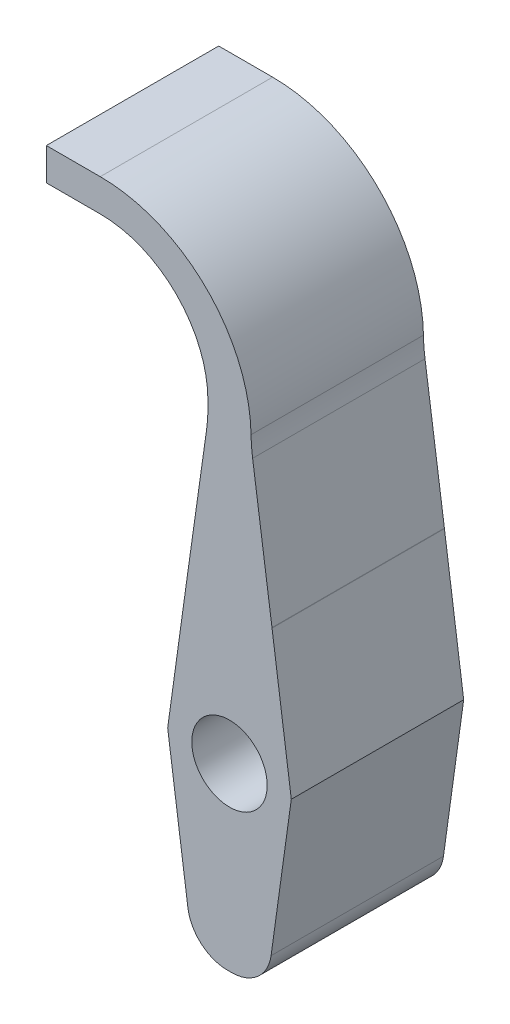
SolidWorks part; units mm, degrees
ref_plane "Front Plane" through (0, 0, 0) normal (0, 0, 1) x (1, 0, 0)
ref_plane "Top Plane" through (0, 0, 0) normal (0, 1, 0) x (1, 0, 0)
ref_plane "Right Plane" through (0, 0, 0) normal (1, 0, 0) x (0, 0, -1)
sketch "Sketch2" plane through (0, 0, 0) normal (0, 0, 1) x (1, 0, 0)
  line L0 (-2, 41.178) -> (2, 41.178)
  line L1 (0, 41.178) -> (0, 42.1099) construction
  line L2 (-0.196, 16.7) -> (0.196, 16.7) construction
  line L3 (-5.5791, 1.1332) -> (-3.8609, 13.5088) construction
  line L4 (3.8609, 13.5088) -> (5.5791, 1.1332) construction
  line L16 (-3.5, 0) -> (3.5, 0) construction
  line L17 (-3.5981, -0.8582) -> (-1.8799, -13.2338)
  line L18 (-0.196, -14.7) -> (0.196, -14.7)
  line L19 (1.8799, 13.2338) -> (3.5981, 0.8582)
  line L20 (-0.196, 14.7) -> (0.196, 14.7)
  line L21 (-3.5981, 0.8582) -> (-1.8799, 13.2338)
  line L22 (1.8799, 13.2338) -> (3.5981, 0.8582)
  line L23 (-0.196, 14.7) -> (0.196, 14.7)
  line L24 (-3.5981, 0.8582) -> (-1.8799, 13.2338)
  line L25 (1.8799, -13.2338) -> (3.5981, -0.8582)
  line L26 (3.5981, 0.8582) -> (3.7172, 0)
  line L27 (3.7172, 0) -> (3.5981, -0.8582)
  line L28 (-3.5981, 0.8582) -> (-3.7172, 0)
  line L29 (-3.7172, 0) -> (-3.5981, -0.8582)
  line L30 (-5.5791, 1.1332) -> (-3.9505, 12.8632)
  line L32 (3.9505, 12.8632) -> (5.5791, 1.1332)
  line L33 (5.5791, 1.1332) -> (5.7364, 0)
  line L34 (5.7364, 0) -> (5.5791, -1.1332)
  line L35 (3.8609, -13.5088) -> (5.5791, -1.1332)
  line L36 (-0.196, -16.7) -> (0.196, -16.7)
  line L37 (-5.5791, -1.1332) -> (-3.8609, -13.5088)
  line L38 (-5.7364, 0) -> (-5.5791, -1.1332)
  line L39 (-5.5791, 1.1332) -> (-5.7364, 0)
  line L40 (-3.9453, 12.9006) -> (-2.1478, 25.6121)
  line L41 (-2, 27.7123) -> (-2, 41.178)
  line L42 (0, -16.7) -> (0, 16.7) construction
  line L43 (3.9453, 12.9006) -> (2.1478, 25.6121)
  line L44 (2, 27.7123) -> (2, 41.178)
  arc A0 (-0.196, 16.7) -> (-3.8609, 13.5088) centre (-0.196, 13) ccw construction
  arc A1 (3.8609, 13.5088) -> (0.196, 16.7) centre (0.196, 13) ccw construction
  arc A2 (-3.9505, 12.8632) -> (-3.9453, 12.9006) centre (10.907, 10.8004) cw
  arc A3 (3.9453, 12.9006) -> (3.9505, 12.8632) centre (-10.907, 10.8004) cw
  arc A4 (2.1478, 25.6121) -> (2, 27.7123) centre (17, 27.7123) cw
  arc A5 (-2.1478, 25.6121) -> (-2, 27.7123) centre (-17, 27.7123) ccw
  circle A10 centre (0, 0) radius 3.5 construction
  arc A11 (-0.196, -14.7) -> (-1.8799, -13.2338) centre (-0.196, -13) cw
  arc A12 (1.8799, 13.2338) -> (0.196, 14.7) centre (0.196, 13) ccw
  arc A13 (-0.196, 14.7) -> (-1.8799, 13.2338) centre (-0.196, 13) ccw
  arc A14 (1.8799, 13.2338) -> (0.196, 14.7) centre (0.196, 13) ccw
  arc A15 (-0.196, 14.7) -> (-1.8799, 13.2338) centre (-0.196, 13) ccw
  arc A16 (1.8799, -13.2338) -> (0.196, -14.7) centre (0.196, -13) cw
  arc A19 (3.8609, -13.5088) -> (0.196, -16.7) centre (0.196, -13) cw
  arc A20 (-0.196, -16.7) -> (-3.8609, -13.5088) centre (-0.196, -13) cw
  point P58 (2, 26.657)
  point P61 (-2, 26.657)
  dimension "D4" = 15
  dimension "D3" = 4
  dimension "D1" = 0.2
  dimension "D2" = 2
extrude "Boss-Extrude1" add sketch "Sketch2" against normal blind 4
sketch "Sketch3" plane through (0, 0, 0) normal (0, 0, 1) x (1, 0, 0)
  line L10 (-3.9505, 12.8632) -> (-5.7364, 0)
  line L11 (-5.7364, 0) -> (-3.8609, -13.5088)
  line L12 (-0.196, -16.7) -> (0.196, -16.7)
  line L13 (3.8609, -13.5088) -> (5.7364, 0)
  line L14 (5.7364, 0) -> (3.9505, 12.8632)
  line L15 (3.9453, 12.9006) -> (2.1478, 25.6121)
  line L16 (2, 27.7123) -> (2, 41.178)
  line L17 (2, 41.178) -> (-2, 41.178)
  line L18 (-2, 41.178) -> (-2, 27.7123)
  line L19 (-2.1478, 25.6121) -> (-3.9453, 12.9006)
  line L20 (-3.9505, 12.8632) -> (-5.7364, 0)
  line L21 (-5.7364, 0) -> (-3.8609, -13.5088)
  line L22 (-0.196, -16.7) -> (0.196, -16.7)
  line L23 (3.8609, -13.5088) -> (5.7364, 0)
  line L24 (5.7364, 0) -> (3.9505, 12.8632)
  line L25 (3.9453, 12.9006) -> (2.1478, 25.6121)
  line L26 (2, 27.7123) -> (2, 41.178)
  line L27 (2, 41.178) -> (-2, 41.178)
  line L28 (-2, 41.178) -> (-2, 27.7123)
  line L29 (-2.1478, 25.6121) -> (-3.9453, 12.9006)
  circle A3 centre (0, 0) radius 3.5
  arc A9 (-3.8609, -13.5088) -> (-0.196, -16.7) centre (-0.196, -13) ccw
  arc A10 (0.196, -16.7) -> (3.8609, -13.5088) centre (0.196, -13) ccw
  arc A11 (3.9505, 12.8632) -> (3.9453, 12.9006) centre (-10.907, 10.8004) ccw
  arc A12 (2, 27.7123) -> (2.1478, 25.6121) centre (17, 27.7123) ccw
  arc A13 (-2.1478, 25.6121) -> (-2, 27.7123) centre (-17, 27.7123) ccw
  arc A14 (-3.9453, 12.9006) -> (-3.9505, 12.8632) centre (10.907, 10.8004) ccw
  arc A15 (-3.8609, -13.5088) -> (-0.196, -16.7) centre (-0.196, -13) ccw
  arc A16 (0.196, -16.7) -> (3.8609, -13.5088) centre (0.196, -13) ccw
  arc A17 (3.9505, 12.8632) -> (3.9453, 12.9006) centre (-10.907, 10.8004) ccw
  arc A18 (2, 27.7123) -> (2.1478, 25.6121) centre (17, 27.7123) ccw
  arc A19 (-2.1478, 25.6121) -> (-2, 27.7123) centre (-17, 27.7123) ccw
  arc A20 (-3.9453, 12.9006) -> (-3.9505, 12.8632) centre (10.907, 10.8004) ccw
  dimension "D1" = 7
  dimension "D2" = 0
extrude "Boss-Extrude2" add sketch "Sketch3" along normal blind 12
sketch "Sketch4" plane through (-2, 0, 0) normal (-1, 0, 0) x (0, 0, 1)
  line L0 (12, 41.178) -> (12, 27.7123) construction
  line L1 (-4, 41.178) -> (12, 41.178)
  line L2 (-4, 41.178) -> (-4, 38.178)
  line L3 (-4, 38.178) -> (12, 38.178)
  line L4 (12, 41.178) -> (12, 38.178)
  dimension "D1" = 3
extrude "Boss-Extrude3" add sketch "Sketch4" along normal blind 15
fillet "Fillet3" radius 10 1 edges at (-2, 38.178, 4)
fillet "Fillet5" radius 14 1 edges at (2, 41.178, 4)
